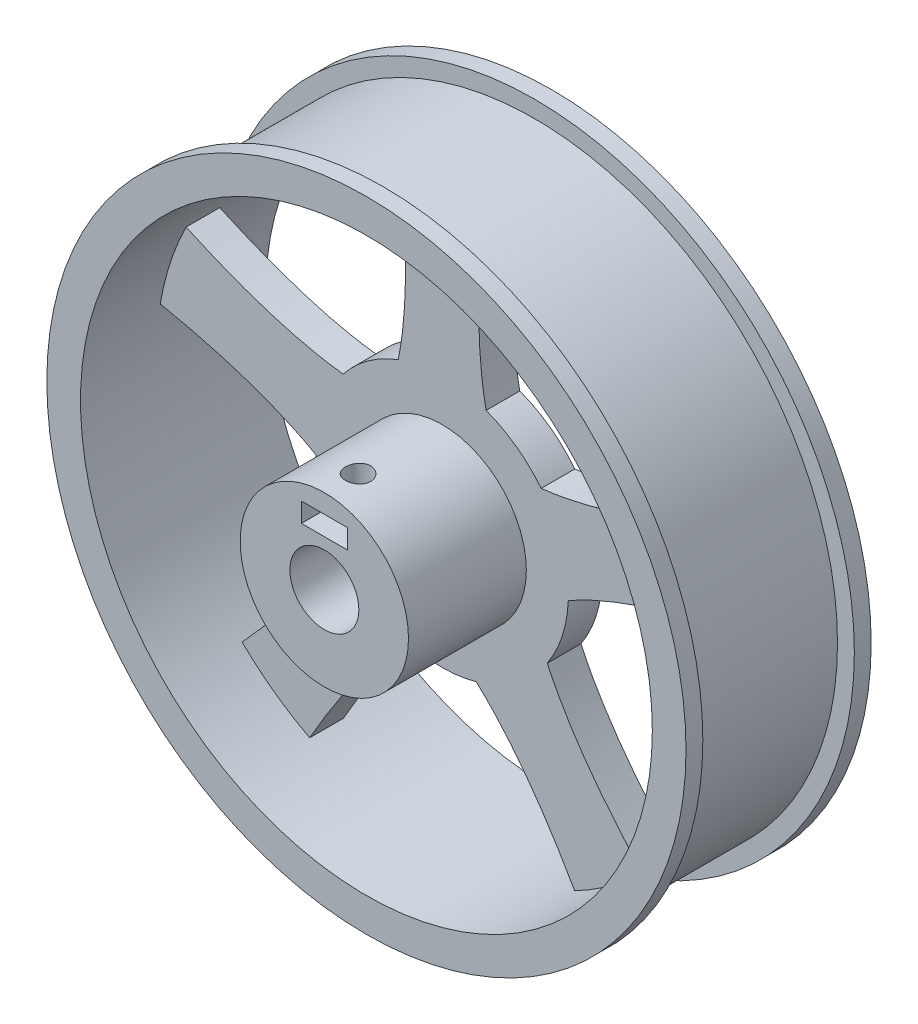
SolidWorks part; units mm, degrees
ref_plane "Front Plane" through (0, 0, 0) normal (0, 0, 1) x (1, 0, 0)
ref_plane "Top Plane" through (0, 0, 0) normal (0, 1, 0) x (1, 0, 0)
ref_plane "Right Plane" through (0, 0, 0) normal (1, 0, 0) x (0, 0, -1)
sketch "Sketch2" plane through (0, 0, 0) normal (1, 0, 0) x (0, 0, -1)
  line L0 (0, 0) -> (0, 35.9709) construction
  line L1 (-9, 35.9709) -> (9, 35.9709)
  line L2 (9, 35.9709) -> (9, 37.9709)
  line L3 (-9, 35.9709) -> (-9, 37.9709)
  line L4 (9, 37.9709) -> (11, 37.9709)
  line L5 (-9, 37.9709) -> (-11, 37.9709)
  line L6 (11, 37.9709) -> (11, 33.9709)
  line L7 (-11, 37.9709) -> (-11, 33.9709)
  line L8 (11, 33.9709) -> (-11, 33.9709)
  line L9 (-10, 0) -> (10, 0)
  point P11 (0, 33.9709)
  point P15 (0, 0)
  dimension "D1" = 18
  dimension "D2" = 2
  dimension "D3" = 2
  dimension "D4" = 4
revolve "Revolve1" add sketch "Sketch2" angle 360 about L9
sketch "Sketch3" plane through (0, 0, 0) normal (0, 0, 1) x (1, 0, 0)
  circle A0 centre (0, 0) radius 15
  circle A1 centre (0, 0) radius 4
  dimension "D1" = 30
  dimension "D2" = 8
extrude "Boss-Extrude1" add sketch "Sketch3" along normal blind 2 and the other way blind 2 separate body contours A0
sketch "Sketch7" plane through (0, 0, 0) normal (0, 0, 1) x (1, 0, 0)
  circle A0 centre (0, 0) radius 4.1
  dimension "D1" = 8.2
sketch "Sketch11" plane through (0, 0, 0) normal (0, 0, 1) x (1, 0, 0)
  line L0 (0, 14.9571) -> (0, 15) construction
  line L1 (0, 33.9709) -> (5, 33.9709)
  line L2 (0, 33.9709) -> (-5, 33.9709)
  line L3 (-5, 33.9709) -> (5, 33.9709)
  line L4 (32.3082, 10.4976) -> (30.7632, 15.2529)
  line L5 (32.3082, 10.4976) -> (33.8533, 5.7423)
  line L6 (19.9676, -27.483) -> (24.0127, -24.5441)
  line L7 (19.9676, -27.483) -> (15.9225, -30.422)
  line L8 (-19.9676, -27.483) -> (-15.9225, -30.422)
  line L9 (-19.9676, -27.483) -> (-24.0127, -24.5441)
  line L10 (-32.3082, 10.4976) -> (-33.8533, 5.7423)
  line L11 (-32.3082, 10.4976) -> (-30.7632, 15.2529)
  circle A0 centre (0, 0) radius 15 construction
  circle A1 centre (0, 0) radius 33.9709 construction
  spline S0 degree 2 poles (5, 33.9709) (3.603, 22.0026) (5.2194, 14.0627) knots 0 0 0 0.277878 0.277878 0.277878
  spline S1 degree 3 poles (5.2194, 14.0627) (2.7127, 14.916) (0.2756, 15.1588) (-2.092, 14.7913) knots 0 0 0 0 0.441009 0.441009 0.441009 0.441009
  spline S2 degree 2 poles (-5, 33.9709) (-3.603, 22.0026) (-5.2194, 14.0627) knots 0 0 0 0.277878 0.277878 0.277878
  spline S3 degree 2 poles (-5.2194, 14.0627) (-2.5171, 14.9241) (0, 14.9571) knots 0 0 0 0.374182 0.374182 0.374182
  spline S4 degree 2 poles (30.7632, 15.2529) (19.8123, 10.2258) (11.7615, 9.3095) knots 0 0 0 0.277878 0.277878 0.277878
  spline S5 degree 2 poles (33.8533, 5.7423) (22.0391, 3.3726) (14.9873, -0.6183) knots 0 0 0 0.277878 0.277878 0.277878
  spline S6 degree 3 poles (14.9873, -0.6183) (15.0242, 2.0294) (14.5021, 4.4223) (13.4209, 6.5604) knots 0 0 0 0 0.441009 0.441009 0.441009 0.441009
  spline S7 degree 2 poles (11.7615, 9.3095) (13.4159, 7.0058) (14.2251, 4.622) knots 0 0 0 0.374182 0.374182 0.374182
  spline S8 degree 2 poles (24.0127, -24.5441) (15.8477, -15.6827) (12.4884, -8.3091) knots 0 0 0 0.277878 0.277878 0.277878
  spline S9 degree 2 poles (15.9225, -30.422) (10.0179, -19.9182) (4.0433, -14.4448) knots 0 0 0 0.277878 0.277878 0.277878
  spline S10 degree 3 poles (4.0433, -14.4448) (6.5728, -13.6618) (8.6872, -12.4257) (10.3866, -10.7367) knots 0 0 0 0 0.441009 0.441009 0.441009 0.441009
  spline S11 degree 2 poles (12.4884, -8.3091) (10.8086, -10.5944) (8.7916, -12.1006) knots 0 0 0 0.374182 0.374182 0.374182
  spline S12 degree 2 poles (-15.9225, -30.422) (-10.0179, -19.9182) (-4.0433, -14.4448) knots 0 0 0 0.277878 0.277878 0.277878
  spline S13 degree 2 poles (-24.0127, -24.5441) (-15.8477, -15.6827) (-12.4884, -8.3091) knots 0 0 0 0.277878 0.277878 0.277878
  spline S14 degree 3 poles (-12.4884, -8.3091) (-10.962, -10.4728) (-9.1331, -12.1018) (-7.0016, -13.196) knots 0 0 0 0 0.441009 0.441009 0.441009 0.441009
  spline S15 degree 2 poles (-4.0433, -14.4448) (-6.7358, -13.5534) (-8.7916, -12.1006) knots 0 0 0 0.374182 0.374182 0.374182
  spline S16 degree 2 poles (-33.8533, 5.7423) (-22.0391, 3.3726) (-14.9873, -0.6183) knots 0 0 0 0.277878 0.277878 0.277878
  spline S17 degree 2 poles (-30.7632, 15.2529) (-19.8123, 10.2258) (-11.7615, 9.3095) knots 0 0 0 0.277878 0.277878 0.277878
  spline S18 degree 3 poles (-11.7615, 9.3095) (-13.3477, 7.1892) (-14.3318, 4.9464) (-14.7138, 2.5811) knots 0 0 0 0 0.441009 0.441009 0.441009 0.441009
  spline S19 degree 2 poles (-14.9873, -0.6183) (-14.9715, 2.2179) (-14.2251, 4.622) knots 0 0 0 0.374182 0.374182 0.374182
  point P49 (0, 0)
  dimension "D1" = 5
  dimension "D2" = 5
  dimension "D3" = 5
extrude "Boss-Extrude3" add sketch "Sketch11" along normal blind 2 and the other way blind 2
sketch "Sketch12" plane through (0, 0, 0) normal (0, 0, 1) x (1, 0, 0)
  circle A0 centre (0, 0) radius 10
  dimension "D1" = 20
extrude "Boss-Extrude4" add sketch "Sketch12" along normal blind 16 contours A0
extrude "Cut-Extrude1" cut sketch "Sketch7" against normal through all both and the other way through all
sketch "Sketch13" plane through (0, 0, 16) normal (0, 0, 1) x (1, 0, 0)
  line L0 (0, 0) -> (0, 5.4641) construction
  line L2 (-2.725, 7.7641) -> (2.725, 7.7641)
  line L3 (-2.725, 7.7641) -> (-2.725, 5.4641)
  line L4 (-2.725, 5.4641) -> (2.725, 5.4641)
  line L5 (2.725, 7.7641) -> (2.725, 5.4641)
  point P7 (0, 5.4641)
  dimension "D1" = 2.3
  dimension "D2" = 5.45
extrude "Cut-Extrude2" cut sketch "Sketch13" against normal blind 4
sketch "Sketch14" plane through (0, 5.4641, 0) normal (0, 1, 0) x (1, 0, 0)
  line L0 (-2.725, -12) -> (2.725, -12) construction
  circle A0 centre (0, -12) radius 1.5
extrude "Cut-Extrude3" cut sketch "Sketch14" against normal blind 4 and the other way blind 6
sketch "Sketch16" plane through (0, 5.4641, 0) normal (0, 1, 0) x (1, 0, 0)
  line L1 (0, -15.1246) -> (2.706, -13.5623)
  line L2 (2.706, -13.5623) -> (2.706, -10.4377)
  line L3 (2.706, -10.4377) -> (0, -8.8754)
  line L4 (0, -8.8754) -> (-2.706, -10.4377)
  line L5 (-2.706, -10.4377) -> (-2.706, -13.5623)
  line L6 (-2.706, -13.5623) -> (0, -15.1246)
  circle A0 centre (0, -12) radius 2.706 construction
  point P1 (0, -15.1246)
extrude "Cut-Extrude4" cut sketch "Sketch16" along normal up to surface (2.3 mm away) up to face at (0, 7.7641, 13.5833)
